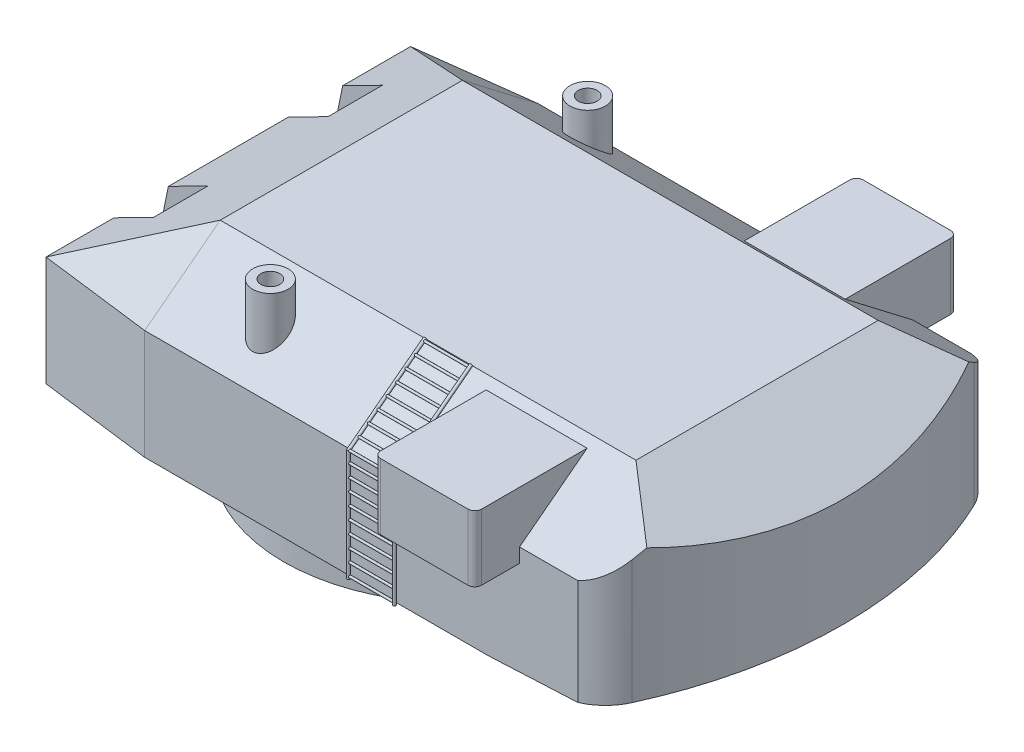
SolidWorks part; units mm, degrees
material "Alloy Steel"
ref_plane "Front Plane" through (0, 0, 0) normal (0, 0, 1) x (1, 0, 0)
ref_plane "Top Plane" through (0, 0, 0) normal (0, 1, 0) x (1, 0, 0)
ref_plane "Right Plane" through (0, 0, 0) normal (1, 0, 0) x (0, 0, -1)
sketch "Sketch1" plane through (0, 0, 0) normal (0, 1, 0) x (1, 0, 0)
  line L0 (-66695.3516, 0) -> (-80549.4066, 0) construction
  line L1 (-77605.4199, -4277.1695) -> (-68184.6625, -4277.1695)
  line L2 (-77605.4199, -4277.1695) -> (-80064.5147, -3965.4533)
  line L3 (-80549.4066, 1783.4396) -> (-80549.4066, -1783.4396)
  line L4 (-77605.4199, 4277.1695) -> (-80064.5147, 3965.4533)
  line L5 (-77605.4199, 4277.1695) -> (-68184.6625, 4277.1695)
  arc A0 (-67561.23, 3723.0073) -> (-67561.23, -3723.0073) centre (-75132.1761, 0) cw
  arc A1 (-67561.23, -3723.0073) -> (-68184.6625, -4277.1695) centre (-68552.5623, -3235.5204) cw
  arc A2 (-80549.4066, -1783.4396) -> (-80064.5147, -3965.4533) centre (-75397.4299, -1783.4396) ccw
  arc A3 (-80549.4066, 1783.4396) -> (-80064.5147, 3965.4533) centre (-75397.4299, 1783.4396) cw
  arc A4 (-67561.23, 3723.0073) -> (-68184.6625, 4277.1695) centre (-68552.5623, 3235.5204) ccw
  point P11 (-77605.4199, -2634.4833)
  point P19 (-80478.6295, -2634.4833)
  point P20 (-71648.0146, -4277.1695)
  point P21 (-69451.462, -4277.1695)
  point P23 (-80478.6295, 2634.4833)
  point P24 (-77605.4199, 2634.4833)
  point P25 (-76905.3564, -4277.1695)
  dimension "D3" = 1104.7095
  dimension "D4" = 8436.8245
  dimension "D6" = 5151.9767
  dimension "D2" = 9420.7574
  dimension "D5" = 2459.0948
  dimension "D7" = 1783.4396
  dimension "D8" = 4277.1695
  dimension "D9" = 3723.0073
extrude "Boss-Extrude1" add sketch "Sketch1" along normal blind 3646.94
sketch "Sketch3" plane through (0, 0, 0) normal (0, 0, 1) x (1, 0, 0)
  line L0 (-77605.4199, 3646.94) -> (-80064.5147, 2388.908)
  line L1 (-80064.5147, 3646.94) -> (-80064.5147, 0) construction
  line L2 (-80064.5147, 2388.908) -> (-80549.4066, 0)
  line L3 (-77605.4199, 3646.94) -> (-80549.4066, 3646.94)
  line L4 (-80549.4066, 3646.94) -> (-80549.4066, 0)
extrude "Cut-Extrude1" cut sketch "Sketch3" against normal through all both and the other way through all
sketch "Sketch4" plane through (0, 0, 0) normal (0, 0, 1) x (1, 0, 0)
  line L0 (-68560.9595, 3646.94) -> (-66695.3516, 2524.7351)
  line L1 (-77605.4199, 3646.94) -> (-68184.6625, 3646.94) construction
  line L2 (-66695.3516, 0) -> (-66695.3516, 3646.94) construction
  line L3 (-66695.3516, 2524.7351) -> (-66695.3516, 3646.94)
  line L4 (-66695.3516, 3646.94) -> (-68560.9595, 3646.94)
extrude "Cut-Extrude2" cut sketch "Sketch4" against normal through all both and the other way through all
sketch "Sketch6" plane through (0, 0, 0) normal (0, 0, 1) x (1, 0, 0)
  line L0 (-70130.854, 0) -> (-66695.3516, 164.0812)
  line L1 (-77605.4199, 0) -> (-68184.6625, 0) construction
  line L2 (-66695.3516, 0) -> (-66695.3516, 2524.7351) construction
  line L3 (-66695.3516, 164.0812) -> (-66695.3516, 0)
  line L4 (-66695.3516, 0) -> (-70130.854, 0)
extrude "Cut-Extrude3" cut sketch "Sketch6" against normal through all both and the other way through all
ref_plane "Plane1" through (-77605.4199, 0, 0) normal (-1, 0, 0) x (0, 0, 1)
sketch "Sketch8" plane through (-77605.4199, 0, 0) normal (-1, 0, 0) x (0, 0, 1)
  line L0 (-4277.1695, 3646.94) -> (-4277.1695, 2388.908)
  line L1 (-4277.1695, 3646.94) -> (4277.1695, 3646.94) construction
  line L2 (0, 0) -> (0, 3646.94) construction
  line L3 (-1783.4396, 0) -> (1783.4396, 0) construction
  line L4 (2634.4833, 3646.94) -> (4277.1695, 2388.908)
  line L5 (4277.1695, 3646.94) -> (4277.1695, 0) construction
  line L6 (2634.4833, 3646.94) -> (4277.1695, 3646.94)
  line L7 (4277.1695, 3646.94) -> (4277.1695, 2388.908)
  line L8 (-2634.4833, 3646.94) -> (-4277.1695, 3646.94)
  line L9 (-2634.4833, 3646.94) -> (-4277.1695, 2388.908)
extrude "Cut-Extrude4" cut sketch "Sketch8" against normal through all both and the other way through all
ref_plane "Plane2" through (-51660.519, 0, -35316.9251) normal (0.8255, 0, 0.5644) x (0.5644, 0, -0.8255)
sketch3d "3DSketch2"
  line L0 (-80064.5147, 2388.908, 3965.4533) -> (-77605.4199, 3646.94, 2634.4833)
  line L1 (-77605.4199, 3646.94, 2634.4833) -> (-77605.4199, 2388.908, 4277.1695)
  line L2 (-77605.4199, 2388.908, 4277.1695) -> (-80064.5147, 2388.908, 3965.4533)
extrude "Cut-Extrude7" cut sketch "3DSketch2" along a picked direction on the side against the normal through all
mirror "Mirror2" about plane through (0, 0, 0) normal (0, 0, 1) of "Cut-Extrude7"
sketch "Sketch12" plane through (0, 0, 0) normal (0, 1, 0) x (1, 0, 0)
  line L0 (-80549.4066, 1783.4396) -> (-80549.4066, -1783.4396) construction
  line L1 (-80549.4066, -1304.3826) -> (-78122.2504, -1304.3826)
  line L2 (-80549.4066, -1304.3826) -> (-80549.4066, -2487.865)
  line L3 (-80549.4066, -2487.865) -> (-78122.2504, -2487.865)
  line L4 (-78122.2504, -1304.3826) -> (-78122.2504, -2487.865)
extrude "Cut-Extrude8" cut sketch "Sketch12" along normal blind 2032 from offset 800
mirror "Mirror3" about plane through (0, 0, 0) normal (0, 0, 1) of "Cut-Extrude8"
extrude "Cut-Extrude9" cut sketch "Sketch13" against normal mid plane 6000
sketch "Sketch13" plane through (0, 0, 0) normal (0, 0, 1) x (1, 0, 0)
  circle A1 centre (-79846.4136, 1633.4781) radius 65.5706
sketch "Sketch14" plane through (0, 0, 0) normal (0, 0, 1) x (1, 0, 0)
  line L0 (-68184.6625, 2388.908) -> (-77605.4199, 2388.908) construction
  line L1 (-71648.0146, 2388.908) -> (-71648.0146, 3514.5073)
  line L2 (-71648.0146, 3514.5073) -> (-69451.462, 3514.5073)
  line L3 (-69451.462, 3514.5073) -> (-69451.462, 2388.908)
  line L4 (-69451.462, 2388.908) -> (-69451.462, 2079.9979)
  line L5 (-69451.462, 2079.9979) -> (-71648.0146, 2079.9979)
  line L6 (-71648.0146, 2079.9979) -> (-71648.0146, 2388.908)
  point P0 (-71648.0146, 2388.908)
  point P1 (-69451.462, 2388.908)
extrude "Boss-Extrude2" add sketch "Sketch14" along normal mid plane 10500
fillet "Fillet1" radius 150 4 edges at (-69451.462, 2797.2526, 5250) (-71648.0146, 2797.2526, 5250) (-69451.462, 2797.2526, -5250) (-71648.0146, 2797.2526, -5250)
sketch "Sketch15" plane through (0, 3646.94, 0) normal (0, 1, 0) x (1, 0, 0)
  line L0 (-77605.4199, 4277.1695) -> (-68184.6625, 4277.1695) construction
  line L1 (-77605.4199, 2634.4833) -> (-77605.4199, 4277.1695) construction
  circle A0 centre (-75697.3976, 3451.2863) radius 385.343
  circle A2 centre (-75697.3976, 3451.2863) radius 205.343
  dimension "D1" = 770.6859
  dimension "D2" = 825.8832
  dimension "D3" = 1908.0223
  dimension "D4" = 180
sketch "Sketch16" plane through (0, 0, 0) normal (0, -1, 0) x (1, 0, 0)
  circle A0 centre (-75132.1761, 0) radius 3725
  dimension "D1" = 7450
extrude "Boss-Extrude3" add sketch "Sketch16" along normal blind 1010
extrude "Boss-Extrude4" add sketch "Sketch15" along normal blind 254 and the other way up to next
mirror "Mirror4" about plane through (0, 0, 0) normal (0, 0, 1) of "Boss-Extrude4"
ref_plane "Plane3" through (-73105.4199, 0, 0) normal (-1, 0, 0) x (0, 0, 1)
sketch "Sketch19" plane through (-73105.4199, 0, 0) normal (-1, 0, 0) x (0, 0, 1)
  line L0 (2634.4833, 3646.94) -> (5798.5093, 3646.94) construction
  line L1 (4277.1695, 0) -> (6143.809, 0) construction
  line L6 (4340.6695, -789.5528) -> (4340.6695, 2420.2597)
  line L8 (4340.6695, 2420.2597) -> (4340.6695, 0)
  line L9 (2673.0924, 3697.3542) -> (4340.6695, 2420.2597)
  line L10 (4340.6695, 3646.94) -> (4340.6695, 2420.2597)
  line L11 (2673.0924, 3697.3542) -> (4340.6695, 2420.2597)
  point P7 (4340.6695, -789.5528)
  dimension "D1" = 63.5
sweep "Sweep1" add path "Sketch19" circular profile diameter 63.5 parameters "D3"=63.5
ref_plane "Plane4" through (-72105.4199, 0, 0) normal (-1, 0, 0) x (0, 0, 1)
sketch "Sketch56" plane through (-72105.4199, 0, 0) normal (-1, 0, 0) x (0, 0, 1)
  line L1 (2673.0924, 3697.3542) -> (4340.6695, 2420.2597) construction
  line L3 (2673.0924, 3697.3542) -> (4340.6695, 2420.2597)
  line L4 (4340.6695, 2420.2597) -> (4340.6695, -789.5528)
  line L5 (4308.9195, -789.5528) -> (4372.4195, -789.5528) construction
sweep "Sweep2" add path "Sketch56" circular profile diameter 63.5 parameters "D3"=63.5
sketch "Sketch69" plane through (-73105.4199, 0, 0) normal (-1, 0, 0) x (0, 0, 1)
  line L0 (2673.0924, 3697.3542) -> (2779.2932, 3616.0215) construction
  line L1 (2692.3969, 3722.5612) -> (2653.7878, 3672.1471) construction
  line L2 (2634.4833, 3646.94) -> (4277.1695, 2388.908) construction
  circle A0 centre (2709.6328, 3669.3701) radius 25.4
  dimension "D1" = 50.8
extrude "Boss-Extrude6" add sketch "Sketch69" against normal up to surface (972.2591 mm away)
pattern_linear "LPattern3" count 9 spacing 256.54 along (0, -0.608, 0.7939) of "Boss-Extrude6"
sketch "Sketch83" plane through (-72105.4199, 0, 0) normal (-1, 0, 0) x (0, 0, 1)
  line L0 (4340.6695, -789.5528) -> (4340.6695, -578.1118) construction
  line L1 (4308.9195, -789.5528) -> (4372.4195, -789.5528) construction
  circle A0 centre (4340.6695, -747.1649) radius 25.4
  dimension "D1" = 50.8
extrude "Boss-Extrude7" add sketch "Sketch83" along normal up to surface (980.95 mm away)
pattern_linear "LPattern4" count 12 spacing 266.7 along (0, 1, 0) of "Boss-Extrude7"
sketch "Sketch84" plane through (-72105.4199, 0, 0) normal (-1, 0, 0) x (0, 0, 1)
  line L1 (4635.4963, 0) -> (3958.6733, 0)
  line L2 (4635.4963, 0) -> (4635.4963, -890.021)
  line L3 (4635.4963, -890.021) -> (3958.6733, -890.021)
  line L4 (3958.6733, 0) -> (3958.6733, -890.021)
extrude "Cut-Extrude10" cut sketch "Sketch84" along normal through all both and the other way through all
